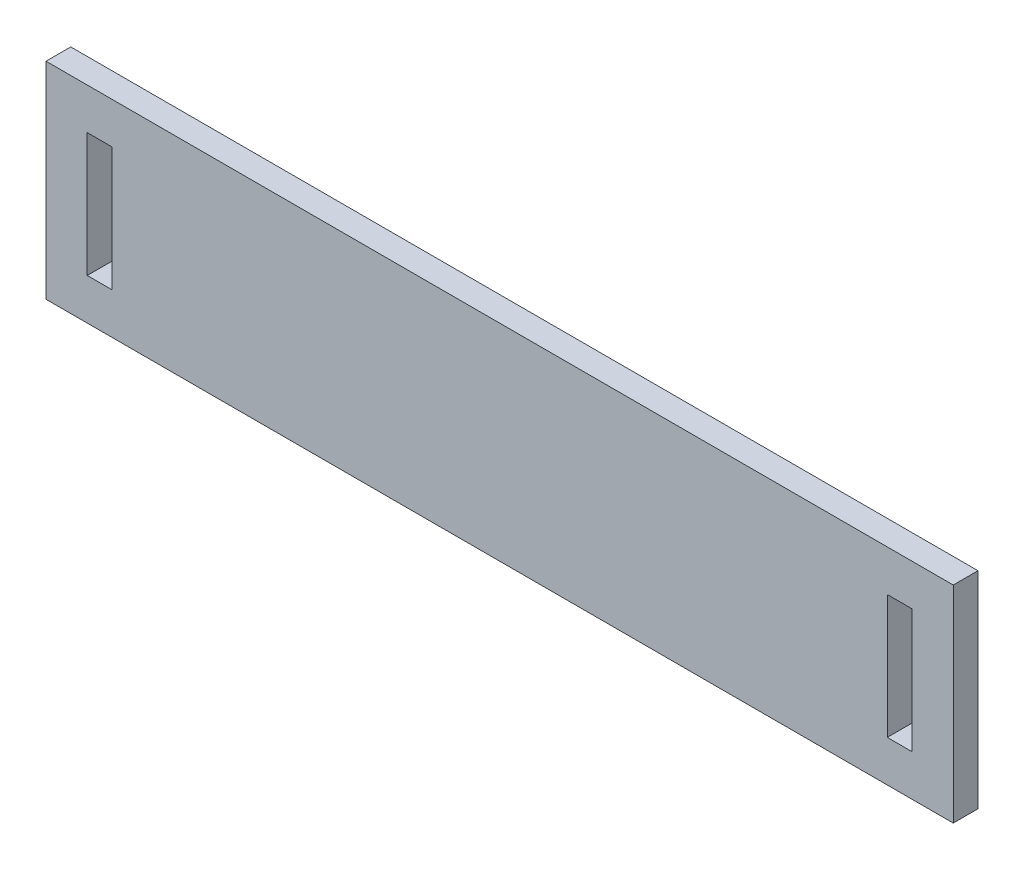
SolidWorks part; units mm, degrees
ref_plane "Front Plane" through (0, 0, 0) normal (0, 0, 1) x (1, 0, 0)
ref_plane "Top Plane" through (0, 0, 0) normal (0, 1, 0) x (1, 0, 0)
ref_plane "Right Plane" through (0, 0, 0) normal (1, 0, 0) x (0, 0, -1)
sketch "Sketch1" plane through (0, 0, 0) normal (0, 0, 1) x (1, 0, 0)
  line L1 (-55, 12.5) -> (55, 12.5)
  line L2 (-55, 12.5) -> (-55, -12.5)
  line L3 (-55, -12.5) -> (55, -12.5)
  line L4 (55, 12.5) -> (55, -12.5)
  line L5 (-55, 12.5) -> (55, -12.5) construction
  line L6 (-55, -12.5) -> (55, 12.5) construction
  point P0 (0, 0)
  dimension "D1" = 25
  dimension "D2" = 110
extrude "Boss-Extrude1" add sketch "Sketch1" along normal blind 3
sketch "Sketch3" plane through (0, 0, 0) normal (0, 0, -1) x (-1, 0, 0)
  line L0 (0, 27.3716) -> (0, -24.4309) construction
  line L1 (50, -7.5) -> (47, -7.5)
  line L2 (-50, 7.5) -> (-47, 7.5)
  line L3 (-50, 7.5) -> (-50, -7.5)
  line L4 (-50, -7.5) -> (-47, -7.5)
  line L5 (-47, 7.5) -> (-47, -7.5)
  line L6 (-50, 7.5) -> (-47, -7.5) construction
  line L7 (-50, -7.5) -> (-47, 7.5) construction
  line L8 (47, 7.5) -> (47, -7.5)
  line L9 (50, 7.5) -> (47, 7.5)
  line L10 (50, 7.5) -> (50, -7.5)
  line L11 (-55, -12.5) -> (-55, 12.5) construction
  line L12 (55, -12.5) -> (-55, -12.5) construction
  point P3 (-48.5, 0)
  dimension "D1" = 3
  dimension "D2" = 15
  dimension "D3" = 5
  dimension "D4" = 5
extrude "Cut-Extrude1" cut sketch "Sketch3" against normal through all
